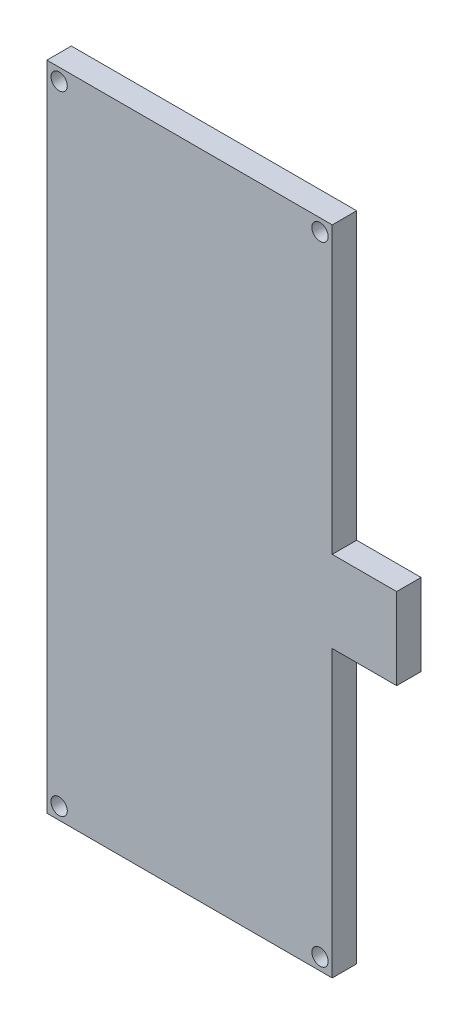
SolidWorks part; units mm, degrees
ref_plane "Front Plane" through (0, 0, 0) normal (0, 0, 1) x (1, 0, 0)
ref_plane "Top Plane" through (0, 0, 0) normal (0, 1, 0) x (1, 0, 0)
ref_plane "Right Plane" through (0, 0, 0) normal (1, 0, 0) x (0, 0, -1)
sketch "Sketch1" plane through (0, 0, 0) normal (0, 0, 1) x (1, 0, 0)
  line L1 (-17.5, -40) -> (17.5, -40)
  line L2 (-17.5, -40) -> (-17.5, 40)
  line L3 (-17.5, 40) -> (17.5, 40)
  line L4 (17.5, -40) -> (17.5, 40)
  line L5 (-17.5, -40) -> (17.5, 40) construction
  line L6 (-17.5, 40) -> (17.5, -40) construction
  point P0 (0, 0)
  dimension "D1" = 80
  dimension "D2" = 35
extrude "Boss-Extrude1" add sketch "Sketch1" along normal blind 3
sketch "Sketch2" plane through (0, 0, 0) normal (0, 0, 1) x (1, 0, 0)
  line L8 (15.4345, 5) -> (25.4, 5)
  line L9 (15.4345, -5) -> (25.4, -5)
  line L11 (25.4, -5) -> (25.4, 5)
  line L16 (15.4345, 5) -> (15.4345, -5)
  point P0 (0, 0)
extrude "Boss-Extrude2" add sketch "Sketch2" along normal blind 3
sketch "Sketch3" plane through (0, 0, 0) normal (0, 0, 1) x (1, 0, 0)
  circle A0 centre (16, 38.5) radius 1
  circle A1 centre (-16, 38.5) radius 1
  circle A2 centre (16, -38.5) radius 1
  circle A3 centre (-16, -38.5) radius 1
  dimension "D1" = 2
  dimension "D2" = 2
extrude "Cut-Extrude2" cut sketch "Sketch3" along normal blind 20.272
